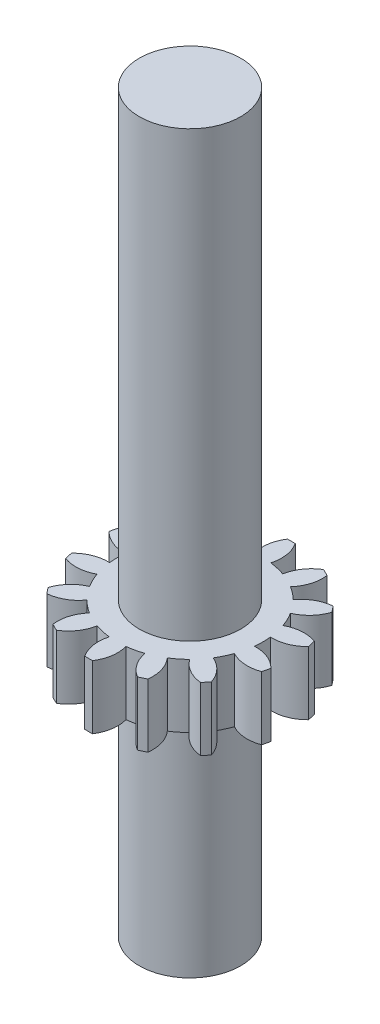
SolidWorks part; units mm, degrees
ref_plane "Front Plane" through (0, 0, 0) normal (0, 0, 1) x (1, 0, 0)
ref_plane "Top Plane" through (0, 0, 0) normal (0, 1, 0) x (1, 0, 0)
ref_plane "Right Plane" through (0, 0, 0) normal (1, 0, 0) x (0, 0, -1)
sketch "Sketch1" plane through (0, 0, 0) normal (0, 1, 0) x (1, 0, 0)
  circle A0 centre (0, 0) radius 0.4
  arc A1 (3.7449, -7.0694) -> (3.0719, -4.8595) centre (0.9684, -6.7075) ccw
  arc A2 (3.0719, -4.8595) -> (4.0541, -4.0762) centre (0, 0) ccw
  arc A3 (4.0541, -4.0762) -> (6.0588, -5.2241) centre (6.3238, -2.4367) ccw
  arc A4 (6.0588, -5.2241) -> (6.4413, -4.7444) centre (0, 0) ccw
  arc A5 (6.4413, -4.7444) -> (4.8761, -3.0454) centre (3.7828, -5.6231) ccw
  arc A6 (4.8761, -3.0454) -> (5.4212, -1.9136) centre (0, 0) ccw
  arc A7 (5.4212, -1.9136) -> (7.7254, -2.0779) centre (6.7548, 0.5485) ccw
  arc A8 (7.7254, -2.0779) -> (7.8619, -1.4798) centre (0, 0) ccw
  arc A9 (7.8619, -1.4798) -> (5.7146, -0.6281) centre (5.8479, -3.4249) ccw
  arc A10 (5.7146, -0.6281) -> (5.7146, 0.6281) centre (0, 0) ccw
  arc A11 (5.7146, 0.6281) -> (7.8619, 1.4798) centre (5.8479, 3.4249) ccw
  arc A12 (7.8619, 1.4798) -> (7.7254, 2.0779) centre (0, 0) ccw
  arc A13 (7.7254, 2.0779) -> (5.4212, 1.9136) centre (6.7548, -0.5485) ccw
  arc A14 (5.4212, 1.9136) -> (4.8761, 3.0454) centre (0, 0) ccw
  arc A15 (4.8761, 3.0454) -> (6.4413, 4.7444) centre (3.7828, 5.6231) ccw
  arc A16 (6.4413, 4.7444) -> (6.0588, 5.2241) centre (0, 0) ccw
  arc A17 (6.0588, 5.2241) -> (4.0541, 4.0762) centre (6.3238, 2.4367) ccw
  arc A18 (4.0541, 4.0762) -> (3.0719, 4.8595) centre (0, 0) ccw
  arc A19 (3.0719, 4.8595) -> (3.7449, 7.0694) centre (0.9684, 6.7075) ccw
  arc A20 (3.7449, 7.0694) -> (3.1921, 7.3355) centre (0, 0) ccw
  arc A21 (3.1921, 7.3355) -> (1.884, 5.4315) centre (4.6404, 4.9392) ccw
  arc A22 (1.884, 5.4315) -> (0.6592, 5.7111) centre (0, 0) ccw
  arc A23 (0.6592, 5.7111) -> (0.3068, 7.9941) centre (-2.0378, 6.4634) ccw
  arc A24 (0.3068, 7.9941) -> (-0.3068, 7.9941) centre (0, 0) ccw
  arc A25 (-0.3068, 7.9941) -> (-0.6592, 5.7111) centre (2.0378, 6.4634) ccw
  arc A26 (-0.6592, 5.7111) -> (-1.884, 5.4315) centre (0, 0) ccw
  arc A27 (-1.884, 5.4315) -> (-3.1921, 7.3355) centre (-4.6404, 4.9392) ccw
  arc A28 (-3.1921, 7.3355) -> (-3.7449, 7.0694) centre (0, 0) ccw
  arc A29 (-3.7449, 7.0694) -> (-3.0719, 4.8595) centre (-0.9684, 6.7075) ccw
  arc A30 (-3.0719, 4.8595) -> (-4.0541, 4.0762) centre (0, 0) ccw
  arc A31 (-4.0541, 4.0762) -> (-6.0588, 5.2241) centre (-6.3238, 2.4367) ccw
  arc A32 (-6.0588, 5.2241) -> (-6.4413, 4.7444) centre (0, 0) ccw
  arc A33 (-6.4413, 4.7444) -> (-4.8761, 3.0454) centre (-3.7828, 5.6231) ccw
  arc A34 (-4.8761, 3.0454) -> (-5.4212, 1.9136) centre (0, 0) ccw
  arc A35 (-5.4212, 1.9136) -> (-7.7254, 2.0779) centre (-6.7548, -0.5485) ccw
  arc A36 (-7.7254, 2.0779) -> (-7.8619, 1.4798) centre (0, 0) ccw
  arc A37 (-7.8619, 1.4798) -> (-5.7146, 0.6281) centre (-5.8479, 3.4249) ccw
  arc A38 (-5.7146, 0.6281) -> (-5.7146, -0.6281) centre (0, 0) ccw
  arc A39 (-5.7146, -0.6281) -> (-7.8619, -1.4798) centre (-5.8479, -3.4249) ccw
  arc A40 (-7.8619, -1.4798) -> (-7.7254, -2.0779) centre (0, 0) ccw
  arc A41 (-7.7254, -2.0779) -> (-5.4212, -1.9136) centre (-6.7548, 0.5485) ccw
  arc A42 (-5.4212, -1.9136) -> (-4.8761, -3.0454) centre (0, 0) ccw
  arc A43 (-4.8761, -3.0454) -> (-6.4413, -4.7444) centre (-3.7828, -5.6231) ccw
  arc A44 (-6.4413, -4.7444) -> (-6.0588, -5.2241) centre (0, 0) ccw
  arc A45 (-6.0588, -5.2241) -> (-4.0541, -4.0762) centre (-6.3238, -2.4367) ccw
  arc A46 (-4.0541, -4.0762) -> (-3.0719, -4.8595) centre (0, 0) ccw
  arc A47 (-3.0719, -4.8595) -> (-3.7449, -7.0694) centre (-0.9684, -6.7075) ccw
  arc A48 (-3.7449, -7.0694) -> (-3.1921, -7.3355) centre (0, 0) ccw
  arc A49 (-3.1921, -7.3355) -> (-1.884, -5.4315) centre (-4.6404, -4.9392) ccw
  arc A50 (-1.884, -5.4315) -> (-0.6592, -5.7111) centre (0, 0) ccw
  arc A51 (-0.6592, -5.7111) -> (-0.3068, -7.9941) centre (2.0378, -6.4634) ccw
  arc A52 (-0.3068, -7.9941) -> (0.3068, -7.9941) centre (0, 0) ccw
  arc A53 (0.3068, -7.9941) -> (0.6592, -5.7111) centre (-2.0378, -6.4634) ccw
  arc A54 (0.6592, -5.7111) -> (1.884, -5.4315) centre (0, 0) ccw
  arc A55 (1.884, -5.4315) -> (3.1921, -7.3355) centre (4.6404, -4.9392) ccw
  arc A56 (3.1921, -7.3355) -> (3.7449, -7.0694) centre (0, 0) ccw
extrude "Boss-Extrude1" add sketch "Sketch1" against normal blind 5
sketch "Sketch2" plane through (0, -5, 0) normal (0, -1, 0) x (1, 0, 0)
  circle A0 centre (0, 0) radius 4
  dimension "D1" = 8
extrude "Boss-Extrude2" add sketch "Sketch2" along normal blind 18 and the other way up to surface (5 mm away) other way up to face at (0, 0, -0.4)
sketch "Sketch3" plane through (0, 0, 0) normal (0, 1, 0) x (1, 0, 0)
  circle A0 centre (0, 0) radius 4
  dimension "D1" = 8
extrude "Boss-Extrude3" add sketch "Sketch3" along normal blind 35
sketch "Sketch4" plane through (0, -23, 0) normal (0, -1, 0) x (1, 0, 0)
  line L0 (-2.5, 0) -> (2.5, 0) construction
  line L1 (-2, -1.5) -> (2, -1.5)
  line L2 (-2, 1.5) -> (2, 1.5)
  line L3 (-2.5, 1.5) -> (2.5, 1.5) construction
  line L4 (-2.5, -1.5) -> (2.5, -1.5) construction
  arc A0 (2, -1.5) -> (2, 1.5) centre (0, 0) ccw
  arc A1 (-2, 1.5) -> (-2, -1.5) centre (0, 0) ccw
  point P6 (0, 0)
  dimension "D1" = 5
  dimension "D2" = 1.5
  dimension "D3" = 1.5
extrude "Cut-Extrude1" cut sketch "Sketch4" against normal up to surface (18 mm away) up to face at (0, -5, 4)
